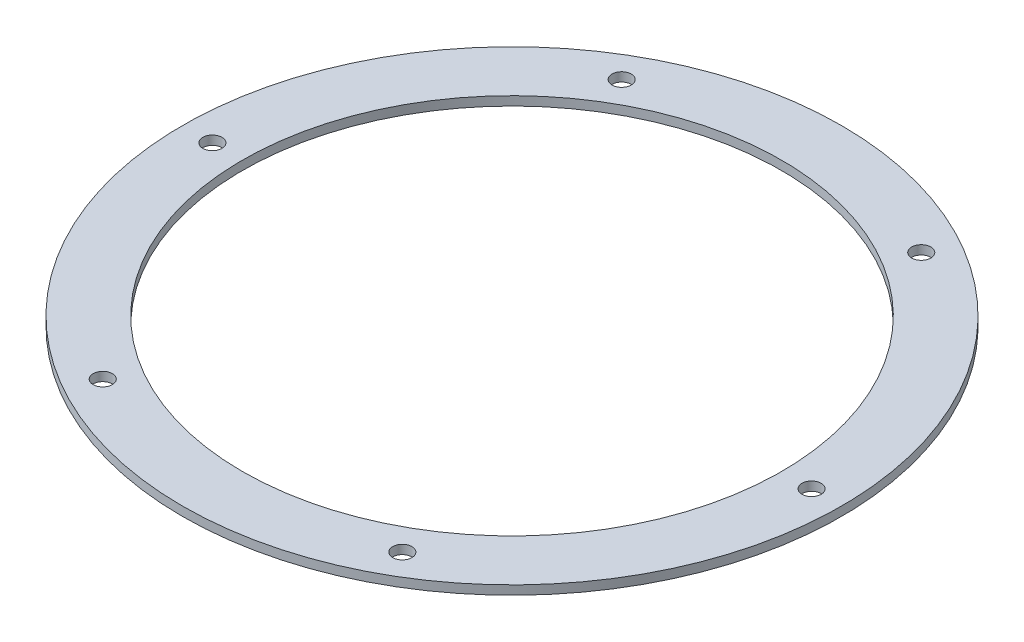
SolidWorks part; units mm, degrees
ref_plane "前视基准面" through (0, 0, 0) normal (0, 0, 1) x (1, 0, 0)
ref_plane "上视基准面" through (0, 0, 0) normal (0, 1, 0) x (1, 0, 0)
ref_plane "右视基准面" through (0, 0, 0) normal (1, 0, 0) x (0, 0, -1)
sketch "草图1" plane through (0, 0, 0) normal (0, 1, 0) x (1, 0, 0)
  circle A0 centre (0, 0) radius 55
  circle A1 centre (0, 0) radius 45
  circle A2 centre (50, 0) radius 1.6
  circle A3 centre (25, -43.3013) radius 1.6
  circle A4 centre (-25, -43.3013) radius 1.6
  circle A5 centre (-50, 0) radius 1.6
  circle A6 centre (-25, 43.3013) radius 1.6
  circle A7 centre (25, 43.3013) radius 1.6
  point P18 (0, 0)
  dimension "D1" = 110
  dimension "D2" = 90
  dimension "D4" = 3.2
  dimension "D3" = 50
extrude "凸台-拉伸1" add sketch "草图1" along normal blind 1.5
